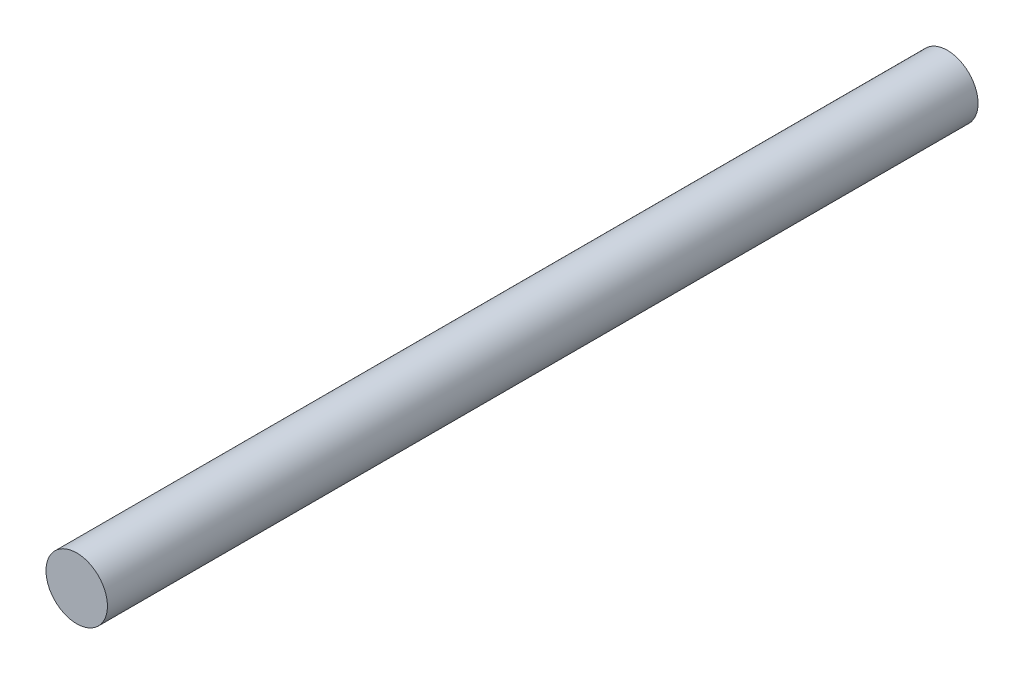
SolidWorks part; units mm, degrees
material "Copper"
ref_plane "Front" through (0, 0, 0) normal (0, 0, 1) x (1, 0, 0)
ref_plane "Top" through (0, 0, 0) normal (0, 1, 0) x (1, 0, 0)
ref_plane "Right" through (0, 0, 0) normal (1, 0, 0) x (0, 0, -1)
sketch "Sketch1" plane through (0, 0, 0) normal (0, 0, 1) x (1, 0, 0)
  circle A0 centre (0, 0) radius 1.5875
  dimension "D1" = 3.175
extrude "Boss-Extrude1" add sketch "Sketch1" along normal mid plane 45
